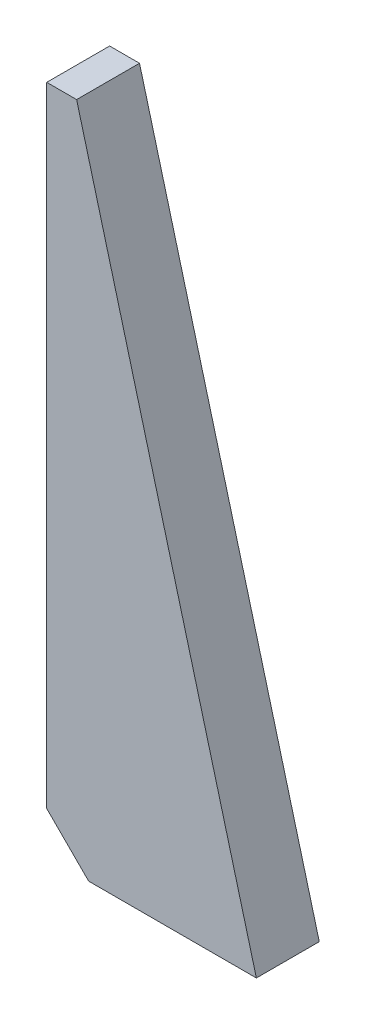
SolidWorks part; units mm, degrees
ref_plane "前基準面" through (0, 0, 0) normal (0, 0, 1) x (1, 0, 0)
ref_plane "上基準面" through (0, 0, 0) normal (0, 1, 0) x (1, 0, 0)
ref_plane "右基準面" through (0, 0, 0) normal (1, 0, 0) x (0, 0, -1)
sketch "草圖1" plane through (0, 0, 0) normal (0, 0, 1) x (1, 0, 0)
  line L0 (0, 0) -> (0, 160)
  line L1 (0, 160) -> (7.1281, 160)
  line L2 (7.1281, 160) -> (50, 0)
  line L3 (50, 0) -> (0, 0)
  dimension "D1" = 160
  dimension "D2" = 50
  dimension "D3" = 75
extrude "填料-伸長1" add sketch "草圖1" along normal blind 15
chamfer "導角1" distance 10 angle 45 1 edges at (0, 0, 7.5)
